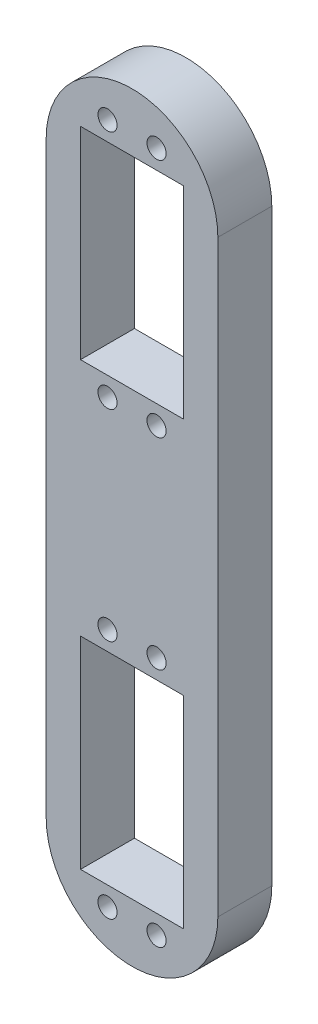
SolidWorks part; units mm, degrees
ref_plane "Front Plane" through (0, 0, 0) normal (0, 0, 1) x (1, 0, 0)
ref_plane "Top Plane" through (0, 0, 0) normal (0, 1, 0) x (1, 0, 0)
ref_plane "Right Plane" through (0, 0, 0) normal (1, 0, 0) x (0, 0, -1)
sketch "Sketch1" plane through (0, 0, 0) normal (0, 0, 1) x (1, 0, 0)
  line L0 (-20, 10) -> (15, 10) construction
  line L2 (-20, 70) -> (-20, -50)
  line L4 (15, 70) -> (15, -50)
  line L5 (-13, 75.5) -> (8, 75.5)
  line L6 (-13, 75.5) -> (-13, 34.5)
  line L7 (-13, 34.5) -> (8, 34.5)
  line L8 (8, 75.5) -> (8, 34.5)
  line L9 (-2.5, 75.5) -> (-2.5, 79.5) construction
  line L10 (-2.5, 79.5) -> (-7.5, 79.5) construction
  line L11 (-2.5, 79.5) -> (2.5, 79.5) construction
  line L12 (-13, 55) -> (8, 55) construction
  line L13 (-7.5, 79.5) -> (-7.5, 30.5) construction
  arc A3 (15, 70) -> (-20, 70) centre (-2.5, 70) ccw
  arc A4 (-20, -50) -> (15, -50) centre (-2.5, -50) ccw
  circle A5 centre (-7.5, 79.5) radius 1.6
  circle A6 centre (2.5, 79.5) radius 1.6
  circle A7 centre (2.5, 30.5) radius 1.6
  circle A8 centre (-7.5, 30.5) radius 1.6
  point P0 (0, 0)
  point P7 (-2.5, 87.5)
  dimension "D4" = 41
  dimension "D5" = 21
  dimension "D7" = 12
  dimension "D11" = 3.2
  dimension "D1" = 120
  dimension "D2" = 35
  dimension "D3" = 120
  dimension "D6" = 7
  dimension "D8" = 4
  dimension "D10" = 5
sketch "Sketch2" plane through (0, 0, 0) normal (0, 0, 1) x (1, 0, 0)
sketch "Sketch3" plane through (0, 0, 0) normal (0, 0, 1) x (1, 0, 0)
extrude "Boss-Extrude1" add sketch "Sketch1" along normal blind 11
sketch "Sketch6" plane through (0, 0, 11) normal (0, 0, 1) x (1, 0, 0)
  line L0 (8, 34.5) -> (8, 75.5) construction
  line L1 (-13, 34.5) -> (8, 34.5) construction
  line L2 (15, -50) -> (15, 70)
  line L3 (-20, 70) -> (-20, -50)
  line L4 (15, -50) -> (15, 70)
  line L5 (-20, 70) -> (-20, -50)
  line L6 (8, 75.5) -> (-13, 75.5) construction
  line L7 (-13, 75.5) -> (-13, 34.5) construction
  line L8 (8, 34.5) -> (8, 75.5)
  line L9 (-13, 34.5) -> (8, 34.5)
  line L10 (8, 75.5) -> (-13, 75.5)
  line L11 (-13, 75.5) -> (-13, 34.5)
  line L12 (-13, 34.5) -> (8, 34.5)
  line L13 (-13, 75.6) -> (8, 75.6)
  line L14 (-13, 75.6) -> (-13, 34.4)
  line L15 (-13, 34.4) -> (8, 34.4)
  line L16 (8, 75.6) -> (8, 34.4)
  line L17 (-13, 75.5) -> (8, 75.5)
  arc A2 (-20, -50) -> (15, -50) centre (-2.5, -50) ccw
  arc A3 (15, 70) -> (-20, 70) centre (-2.5, 70) ccw
  arc A4 (-20, -50) -> (15, -50) centre (-2.5, -50) ccw
  arc A5 (15, 70) -> (-20, 70) centre (-2.5, 70) ccw
  line M15 (8, 34.5) -> (-13, 34.5)
  line M17 (-13, 75.5) -> (8, 75.5)
  dimension "D2" = 0.1
  dimension "D3" = 0.1
  dimension "D1" = 0
extrude "Cut-Extrude1" cut sketch "Sketch6" against normal through all contours L16 L13 L14 M17 | L16 L14 L15 M15
sketch "Sketch7" plane through (0, 0, 0) normal (0, 0, -1) x (-1, 0, 0)
  line L0 (13, 34.4) -> (-8, 34.4) construction
  line L1 (13, 75.6) -> (13, 34.4) construction
  line L2 (13, 75.6) -> (-8, 75.6) construction
  line L3 (-8, 34.4) -> (-8, 75.6) construction
  line L4 (13, 34.4) -> (-8, 34.4)
  line L5 (13, 75.6) -> (13, 34.4)
  line L6 (13, 75.6) -> (-8, 75.6)
  line L7 (-8, 34.4) -> (-8, 75.6)
  line L8 (-15, 10) -> (20, 10) construction
  line L9 (-15, -50) -> (-15, 70) construction
  line L10 (20, 70) -> (20, -50) construction
  line L11 (13, -55.6) -> (13, -14.4)
  line L12 (13, -55.6) -> (-8, -55.6)
  line L13 (-8, -14.4) -> (-8, -55.6)
  line L14 (13, -14.4) -> (-8, -14.4)
  circle A0 centre (7.5, 79.5) radius 1.6 construction
  circle A1 centre (-2.5, 79.5) radius 1.6 construction
  circle A2 centre (7.5, 30.5) radius 1.6 construction
  circle A3 centre (-2.5, 30.5) radius 1.6 construction
  circle A4 centre (7.5, 79.5) radius 1.6
  circle A5 centre (-2.5, 79.5) radius 1.6
  circle A6 centre (7.5, 30.5) radius 1.6
  circle A7 centre (-2.5, 30.5) radius 1.6
  circle A8 centre (7.5, -10.5) radius 1.6
  circle A9 centre (-2.5, -10.5) radius 1.6
  circle A10 centre (-2.5, -59.5) radius 1.6
  circle A11 centre (7.5, -59.5) radius 1.6
extrude "Cut-Extrude2" cut sketch "Sketch7" against normal up to surface (11 mm away) contours L11 L14 L13 L12 | A9 | A8 | A10 | A11 up to face at (4.1, 30.5, 11)
sketch "Sketch8" plane through (0, 0, 11) normal (0, 0, 1) x (1, 0, 0)
  line L0 (-20, 10) -> (15, 10) construction
  line L1 (-20, 70) -> (-20, -50) construction
  line L2 (15, -50) -> (15, 70) construction
  line L3 (-2.5, 87.5) -> (-2.5, -67.5) construction
  line L4 (-13, 55) -> (8, 55) construction
  line L5 (-13, 75.6) -> (-13, 34.4) construction
  line L6 (8, 34.4) -> (8, 75.6) construction
  arc A0 (15, 70) -> (-20, 70) centre (-2.5, 70) ccw construction
  arc A1 (-20, -50) -> (15, -50) centre (-2.5, -50) ccw construction
  circle A2 centre (-7.5, 79.5) radius 1.95
  circle A3 centre (2.5, 79.5) radius 1.95
  circle A4 centre (2.5, 30.5) radius 1.95
  circle A5 centre (-7.5, 30.5) radius 1.95
  circle A6 centre (2.5, -10.5) radius 1.95
  circle A7 centre (-7.5, -10.5) radius 1.95
  circle A8 centre (2.5, -59.5) radius 1.95
  circle A9 centre (-7.5, -59.5) radius 1.95
  dimension "D1" = 3.9
extrude "Cut-Extrude3" cut sketch "Sketch8" against normal up to surface (11 mm away) up to face at (-2.5, -35, 0)
